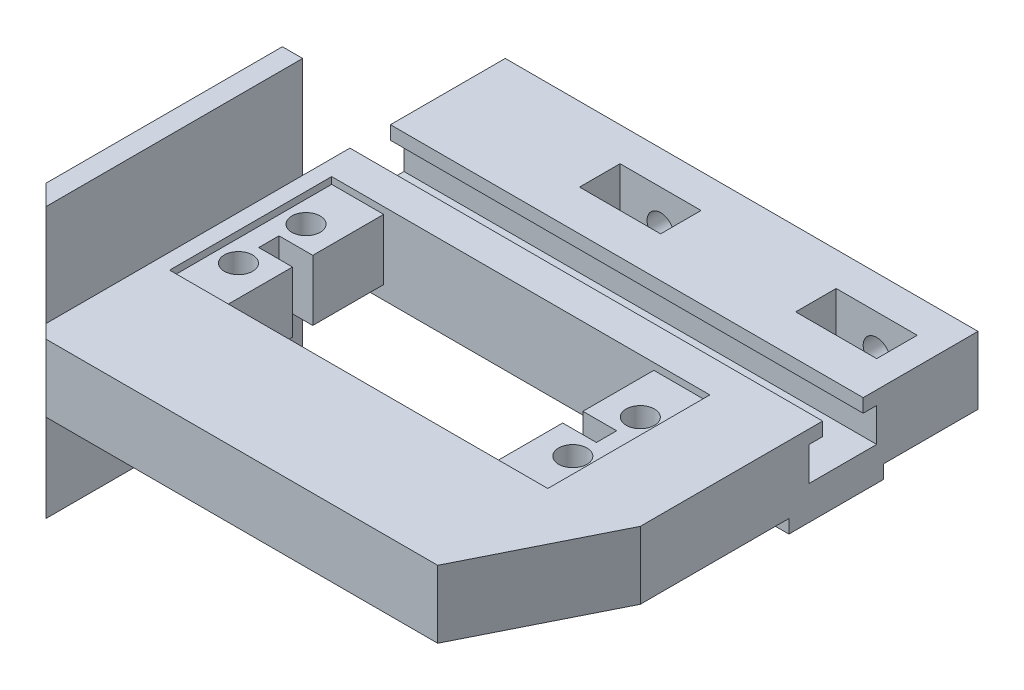
SolidWorks part; units mm, degrees
material "ABS"
ref_plane "前基準面" through (0, 0, 0) normal (0, 0, 1) x (1, 0, 0)
ref_plane "上基準面" through (0, 0, 0) normal (0, 1, 0) x (1, 0, 0)
ref_plane "右基準面" through (0, 0, 0) normal (1, 0, 0) x (0, 0, -1)
sketch "草圖1" plane through (0, 0, 0) normal (0, 1, 0) x (1, 0, 0)
  line L1 (-30, 12) -> (10, 12)
  line L2 (-30, 12) -> (-30, -12)
  line L3 (-30, -12) -> (10, -12)
  line L4 (10, 12) -> (10, -12)
  line L5 (-40, 30) -> (40, 30)
  line L6 (-40, 30) -> (-40, -30)
  line L7 (-40, -30) -> (40, -30)
  line L8 (40, 30) -> (40, -30)
  circle A0 centre (0, 0) radius 1.6622
  circle A1 centre (15, 5) radius 2.1
  circle A2 centre (15, -5) radius 2.1
  circle A3 centre (-34.5, 5) radius 2.1
  circle A4 centre (-34.5, -5) radius 2.1
  dimension "D4" = 4.2
  dimension "D5" = 4.2
  dimension "D6" = 4.2
  dimension "D7" = 4.2
  dimension "D1" = 10
  dimension "D2" = 15
  dimension "D3" = 5
  dimension "D8" = 49.5
  dimension "D9" = 49.5
  dimension "D10" = 40
  dimension "D11" = 5
  dimension "D12" = 24
  dimension "D13" = 12
  dimension "D14" = 30
  dimension "D15" = 30
  dimension "D16" = 40
  dimension "D17" = 40
extrude "填料-伸長1" add sketch "草圖1" along normal blind 10 contours L8 L5 L6 L7 A4 A3 A2 A1 L1 L4 L3 L2
sketch "草圖4" plane through (40, 0, 0) normal (1, 0, 0) x (0, 0, -1)
  line L1 (30, 10) -> (-30, 10) construction
  line L9 (17, 10) -> (17, 8)
  line L10 (17, 8) -> (15, 8)
  line L11 (15, 8) -> (15, 3)
  line L12 (15, 3) -> (25, 3)
  line L13 (25, 3) -> (25, 8)
  line L14 (25, 8) -> (23, 8)
  line L15 (23, 8) -> (23, 10)
  line L16 (23, 10) -> (17, 10)
  line L17 (30, 0) -> (-30, 0) construction
  line L18 (30, 10) -> (30, 0) construction
  dimension "D1" = 10
  dimension "D5" = 2
  dimension "D6" = 2
  dimension "D7" = 3
  dimension "D11" = 5
  dimension "D12" = 5
  dimension "D13" = 5
extrude "除料-伸長1" cut sketch "草圖4" against normal blind 80
sketch "草圖5" plane through (0, 10, 0) normal (0, 1, 0) x (1, 0, 0)
  line L8 (10, 1.5) -> (10, -1.5)
  line L9 (10, 12) -> (10, -12) construction
  line L10 (10, -1.5) -> (15, -1.5)
  line L11 (15, -1.5) -> (15, 1.5)
  line L12 (15, 1.5) -> (10, 1.5)
  line L13 (-30, 1.5) -> (-35, 1.5)
  line L14 (-30, 12) -> (-30, -12) construction
  line L15 (-35, 1.5) -> (-35, -1.5)
  line L16 (-35, -1.5) -> (-30, -1.5)
  line L17 (-30, -1.5) -> (-30, 1.5)
  line L18 (-40, 17) -> (40, 17) construction
  dimension "D3" = 3
  dimension "D1" = 5
  dimension "D2" = 3
  dimension "D4" = 5
  dimension "D5" = 15.5
extrude "除料-伸長2" cut sketch "草圖5" against normal blind 80
sketch "草圖7" plane through (0, 10, 0) normal (0, 1, 0) x (1, 0, 0)
  line L1 (-37.7, 12) -> (18.3, 12)
  line L2 (-37.7, 12) -> (-37.7, -12)
  line L3 (-37.7, -12) -> (18.3, -12)
  line L4 (18.3, 12) -> (18.3, -12)
  circle A0 centre (15, -5) radius 2.1 construction
  dimension "D1" = 24
  dimension "D3" = 56
  dimension "D4" = 3.3
extrude "除料-伸長3" cut sketch "草圖7" against normal blind 1 contours L1 L4 L3 L2
sketch "草圖8" plane through (-40, 0, 0) normal (-1, 0, 0) x (0, 0, 1)
  line L0 (30, 25) -> (30, -15)
  line L5 (30, -15) -> (-10, -15)
  line L6 (-10, -15) -> (-10, 25)
  line L7 (-10, 25) -> (30, 25)
  point P0 (30, 10)
  point P1 (30, 0)
  dimension "D1" = 40
  dimension "D2" = 40
  dimension "D3" = 15
extrude "填料-伸長2" add sketch "草圖8" along normal blind 3
sketch "草圖9" plane through (0, 10, 0) normal (0, 1, 0) x (1, 0, 0)
  line L0 (-40, -30) -> (40, -30) construction
  line L1 (40, 30) -> (30, 30)
  line L2 (40, 30) -> (40, -30)
  line L3 (40, -30) -> (30, -30)
  line L4 (30, 30) -> (30, -30)
  dimension "D1" = 10
extrude "除料-伸長4" cut sketch "草圖9" against normal blind 10
sketch "草圖22" plane through (0, 10, 0) normal (0, 1, 0) x (1, 0, 0)
  line L0 (-43, -25) -> (-43, -30)
  line L1 (-43, -30) -> (-43, 10) construction
  line L2 (-43, -30) -> (-38, -30)
  line L3 (-40, -30) -> (30, -30) construction
  line L4 (-38, -30) -> (-43, -25)
  dimension "D1" = 5
  dimension "D2" = 5
extrude "除料-伸長11" cut sketch "草圖22" against normal blind 28
sketch "草圖23" plane through (0, 25, 0) normal (0, 1, 0) x (1, 0, 0)
  line L0 (-43, -30) -> (-38, -30)
  line L1 (-38, -30) -> (30, -30) construction
  line L2 (-38, -30) -> (-43, -25)
  line L3 (-43, -30) -> (-43, 10) construction
  line L4 (-43, -25) -> (-43, -30)
  dimension "D1" = 5
  dimension "D2" = 5
extrude "除料-伸長12" cut sketch "草圖23" against normal blind 41
sketch "草圖24" plane through (-40, 0, 0) normal (-1, 0, 0) x (0, 0, 1)
  line L0 (-25, 3) -> (-25, 8) construction
  line L1 (-30, 10) -> (-40, 10)
  line L2 (-30, 10) -> (-30, 0)
  line L3 (-30, 0) -> (-40, 0)
  line L4 (-40, 10) -> (-40, 0)
  dimension "D1" = 15
extrude "填料-伸長3" add sketch "草圖24" against normal up to vertex (70 mm away)
sketch "草圖25" plane through (0, 10, 0) normal (0, 1, 0) x (1, 0, 0)
  line L0 (-40, 40) -> (-40, 23) construction
  line L1 (-18, 35) -> (-6, 35)
  line L2 (-18, 35) -> (-18, 29)
  line L3 (-18, 29) -> (-6, 29)
  line L4 (-6, 35) -> (-6, 29)
  line L5 (14, 35) -> (26, 35)
  line L6 (14, 35) -> (14, 29)
  line L7 (14, 29) -> (26, 29)
  line L8 (26, 35) -> (26, 29)
  line L9 (30, 40) -> (30, 23) construction
  line L10 (-40, 23) -> (30, 23) construction
  dimension "D1" = 6
  dimension "D2" = 6
  dimension "D3" = 12
  dimension "D4" = 12
  dimension "D5" = 22
  dimension "D6" = 4
  dimension "D7" = 6
  dimension "D8" = 6
extrude "除料-伸長13" cut sketch "草圖25" against normal blind 9
sketch "草圖26" plane through (0, 0, -40) normal (0, 0, -1) x (-1, 0, 0)
  line L0 (-30, 10) -> (-30, 0) construction
  circle A0 centre (-20, 4.7234) radius 2
  circle A1 centre (12, 4.7234) radius 2
  dimension "D1" = 32
  dimension "D2" = 4
  dimension "D3" = 4
  dimension "D4" = 10
extrude "除料-伸長14" cut sketch "草圖26" against normal blind 8
sketch "草圖27" plane through (0, 10, 0) normal (0, 1, 0) x (1, 0, 0)
  line L0 (30, -10) -> (20, -30)
  line L1 (30, 17) -> (30, -30) construction
  line L2 (-38, -30) -> (30, -30) construction
  line L3 (20, -30) -> (30, -30)
  line L4 (30, -30) -> (30, -10)
  dimension "D2" = 20
  dimension "D3" = 10
extrude "除料-伸長15" cut sketch "草圖27" against normal up to next
sketch "草圖28" plane through (0, 0, -40) normal (0, 0, -1) x (-1, 0, 0)
  line L0 (40, 0) -> (40, -15) construction
  line L1 (-30, 0) -> (40, 0)
  line L2 (-30, 0) -> (-30, -2)
  line L3 (-30, -2) -> (40, -2)
  line L4 (40, 0) -> (40, -2)
  line L5 (40, 3) -> (-30, 3) construction
  dimension "D1" = 2
extrude "填料-伸長4" add sketch "草圖28" against normal up to vertex
sketch "草圖29" plane through (30, 0, 0) normal (1, 0, 0) x (0, 0, -1)
  line L1 (40, -2) -> (26, -2)
  line L2 (40, -2) -> (40, 0)
  line L3 (40, 0) -> (26, 0)
  line L4 (26, -2) -> (26, 0)
  dimension "D1" = 2
  dimension "D2" = 14
extrude "除料-伸長16" cut sketch "草圖29" against normal up to vertex
